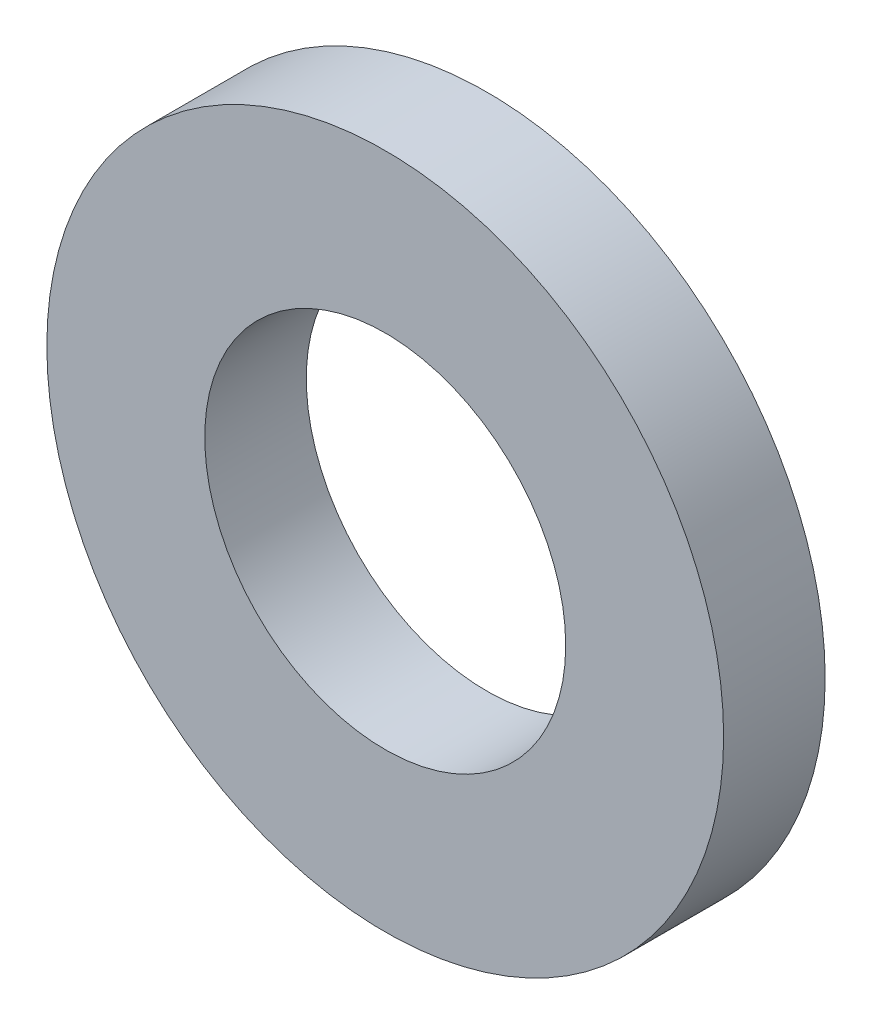
SolidWorks part; units mm, degrees
ref_plane "Plan de face" through (0, 0, 0) normal (0, 0, 1) x (1, 0, 0)
ref_plane "Plan de dessus" through (0, 0, 0) normal (0, 1, 0) x (1, 0, 0)
ref_plane "Plan de droite" through (0, 0, 0) normal (1, 0, 0) x (0, 0, -1)
sketch "Esquisse1" plane through (0, 0, 0) normal (0, 0, 1) x (1, 0, 0)
  circle A0 centre (0, 0) radius 3.2
  circle A1 centre (0, 0) radius 6
  dimension "D1" = 6.4
  dimension "D2" = 12
extrude "Boss.-Extru.1" add sketch "Esquisse1" along normal blind 1.8
